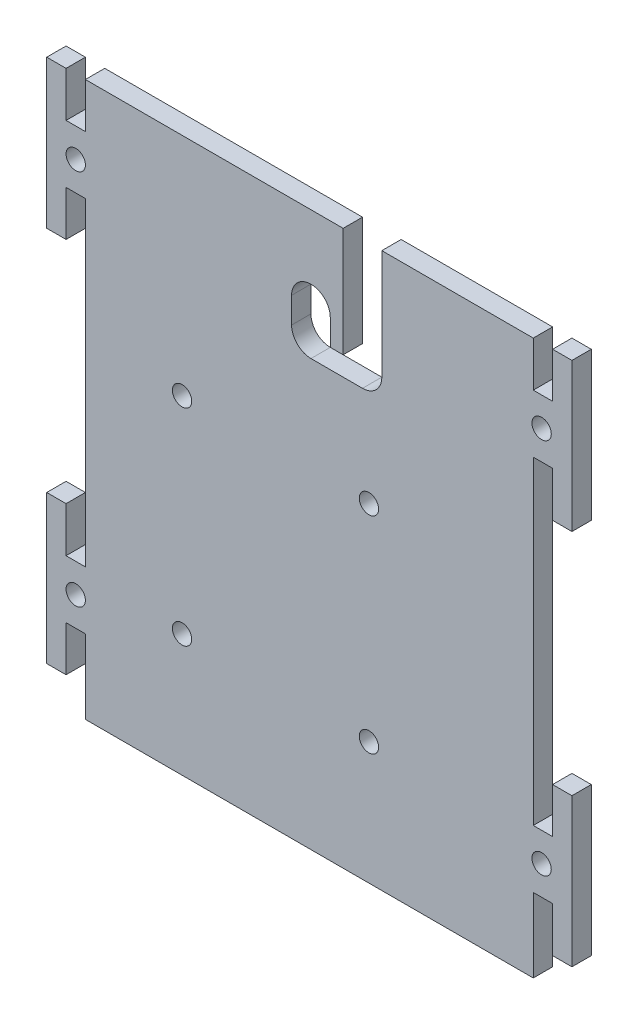
SolidWorks part; units mm, degrees
ref_plane "前视基准面" through (0, 0, 0) normal (0, 0, 1) x (1, 0, 0)
ref_plane "上视基准面" through (0, 0, 0) normal (0, 1, 0) x (1, 0, 0)
ref_plane "右视基准面" through (0, 0, 0) normal (1, 0, 0) x (0, 0, -1)
other "Configuration Table"
sketch "草图1" plane through (0, 0, 0) normal (0, 0, 1) x (1, 0, 0)
  line L0 (0, 0) -> (40, 0)
  line L1 (40, 0) -> (40, -17)
  line L2 (40, -17) -> (38, -17)
  line L3 (38, -17) -> (38, -13)
  line L4 (32, -13) -> (32, -17)
  line L5 (35, -20) -> (43, -20)
  line L6 (46, -17) -> (46, 0)
  line L7 (0, 0) -> (0, -7)
  line L8 (0, -7) -> (-3, -7)
  line L9 (-3, -7) -> (-3, 0)
  line L10 (-3, 0) -> (-6, 0)
  line L11 (-6, 0) -> (-6, -23)
  line L12 (-6, -23) -> (-3, -23)
  line L13 (-3, -23) -> (-3, -16)
  line L14 (-3, -16) -> (0, -16)
  line L15 (0, -16) -> (0, -65.5)
  line L16 (0, -65.5) -> (-3, -65.5)
  line L17 (-3, -65.5) -> (-3, -58.5)
  line L18 (-3, -58.5) -> (-6, -58.5)
  line L19 (-6, -58.5) -> (-6, -81.5)
  line L20 (-6, -81.5) -> (-3, -81.5)
  line L21 (-3, -81.5) -> (-3, -74.5)
  line L22 (-3, -74.5) -> (0, -74.5)
  line L23 (0, -74.5) -> (0, -86)
  line L24 (0, -86) -> (69.5, -86)
  line L25 (69.5, -86) -> (69.5, -74.5)
  line L26 (69.5, -74.5) -> (72.5, -74.5)
  line L27 (72.5, -74.5) -> (72.5, -81.5)
  line L28 (72.5, -81.5) -> (75.5, -81.5)
  line L29 (75.5, -81.5) -> (75.5, -58.5)
  line L30 (75.5, -58.5) -> (72.5, -58.5)
  line L31 (72.5, -58.5) -> (72.5, -65.5)
  line L32 (72.5, -65.5) -> (69.5, -65.5)
  line L33 (69.5, -65.5) -> (69.5, -16)
  line L34 (69.5, -16) -> (72.5, -16)
  line L35 (72.5, -16) -> (72.5, -23)
  line L36 (72.5, -23) -> (75.5, -23)
  line L37 (75.5, -23) -> (75.5, 0)
  line L38 (75.5, 0) -> (72.5, 0)
  line L39 (72.5, 0) -> (72.5, -7)
  line L40 (72.5, -7) -> (69.5, -7)
  line L41 (69.5, -7) -> (69.5, 0)
  line L42 (69.5, 0) -> (46, 0)
  line L43 (0, -47.3374) -> (15, -47.3374) construction
  line L44 (15, -86) -> (15, -67) construction
  line L45 (15, -67) -> (44, -67) construction
  line L46 (15, -67) -> (15, -35) construction
  line L47 (-1.5, -74.5) -> (-1.5, -70) construction
  line L48 (-1.5, -16) -> (-1.5, -11.5) construction
  arc A0 (38, -13) -> (32, -13) centre (35, -13) ccw
  arc A1 (32, -17) -> (35, -20) centre (35, -17) ccw
  arc A2 (43, -20) -> (46, -17) centre (43, -17) ccw
  circle A3 centre (15, -67) radius 1.5
  circle A4 centre (44, -67) radius 1.5
  circle A5 centre (15, -35) radius 1.5
  circle A6 centre (44, -35) radius 1.5
  circle A7 centre (-1.5, -70) radius 1.5
  circle A8 centre (70.7931, -70) radius 1.5
  circle A9 centre (-1.5, -11.5) radius 1.5
  circle A10 centre (70.7931, -11.5) radius 1.5
  dimension "D5" = 3
  dimension "D6" = 4
  dimension "D7" = 3
  dimension "D9" = 3
  dimension "D17" = 49.5
  dimension "D32" = 3
  dimension "D34" = 3
  dimension "D36" = 3
  dimension "D37" = 3
  dimension "D41" = 3
  dimension "D42" = 3
  dimension "D44" = 3
  dimension "D45" = 3
  dimension "D1" = 40
  dimension "D2" = 17
  dimension "D3" = 2
  dimension "D4" = 4
  dimension "D8" = 8
  dimension "D10" = 17
  dimension "D11" = 6
  dimension "D12" = 7
  dimension "D13" = 3
  dimension "D14" = 3
  dimension "D15" = 23
  dimension "D16" = 7
  dimension "D18" = 7
  dimension "D19" = 23
  dimension "D20" = 7
  dimension "D21" = 11.5
  dimension "D22" = 69.5
  dimension "D23" = 3
  dimension "D24" = 7
  dimension "D25" = 3
  dimension "D26" = 23
  dimension "D27" = 3
  dimension "D28" = 7
  dimension "D29" = 3
  dimension "D30" = 15
  dimension "D31" = 19
  dimension "D33" = 29
  dimension "D35" = 32
  dimension "D38" = 32
  dimension "D39" = 29
  dimension "D40" = 4.5
  dimension "D43" = 4.5
extrude "凸台-拉伸1" add sketch "草图1" along normal blind 3
